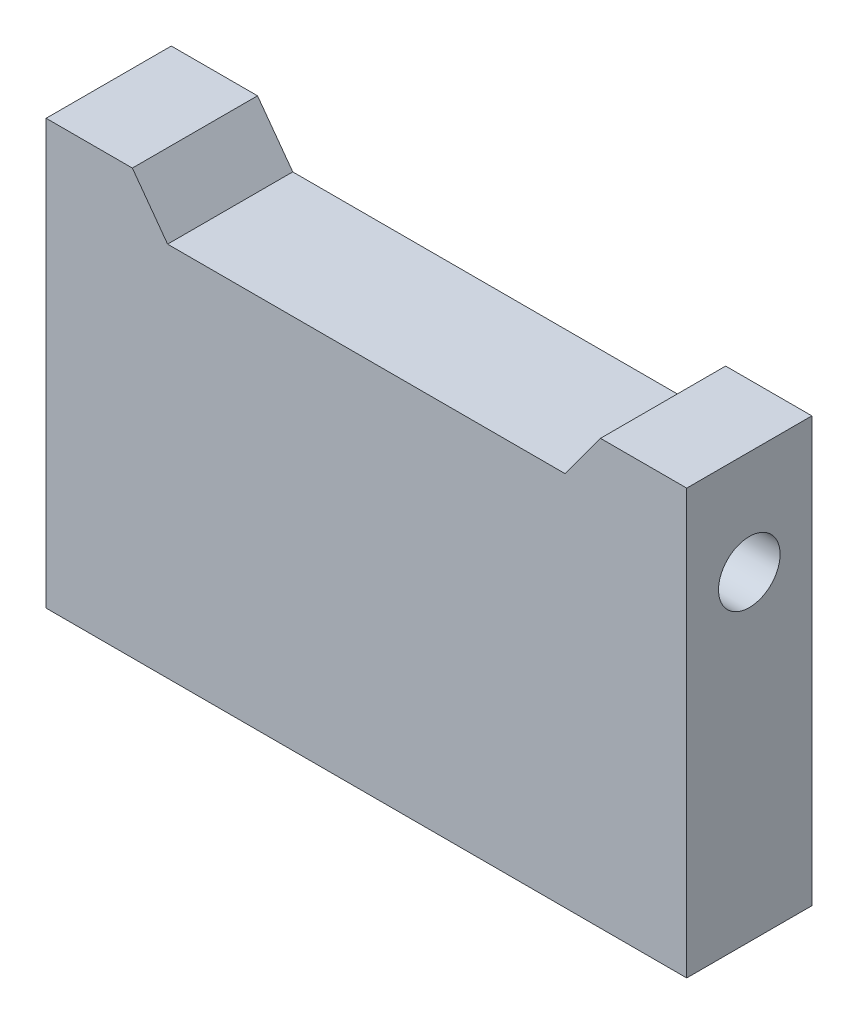
SolidWorks part; units mm, degrees
ref_plane "Piano frontale" through (0, 0, 0) normal (0, 0, 1) x (1, 0, 0)
ref_plane "Piano superiore" through (0, 0, 0) normal (0, 1, 0) x (1, 0, 0)
ref_plane "Piano destro" through (0, 0, 0) normal (1, 0, 0) x (0, 0, -1)
sketch "Schizzo1" plane through (0, 0, 0) normal (0, 0, 1) x (1, 0, 0)
  line L1 (-13, -8.61) -> (13, -8.61)
  line L2 (-13, -8.61) -> (-13, 8.61)
  line L3 (-13, 8.61) -> (13, 8.61)
  line L4 (13, -8.61) -> (13, 8.61)
  line L5 (-13, -8.61) -> (13, 8.61) construction
  line L6 (-13, 8.61) -> (13, -8.61) construction
  point P0 (0, 0)
  dimension "D1" = 26
  dimension "D2" = 17.22
extrude "Estrusione-Estrusione1" add sketch "Schizzo1" against normal blind 5.08
sketch "Schizzo2" plane through (0, 0, 0) normal (0, 0, 1) x (1, 0, 0)
  line L0 (13, 8.61) -> (-13, 8.61) construction
  line L1 (-9.5, 8.61) -> (9.5, 8.61)
  line L2 (0, 8.61) -> (0, -8.61) construction
  line L3 (-13, -8.61) -> (13, -8.61) construction
  line L4 (-9.5, 8.61) -> (-8.07, 6.65)
  line L5 (-8.07, 6.65) -> (8.07, 6.65)
  line L6 (9.5, 8.61) -> (8.07, 6.65)
  line L7 (13, -8.61) -> (13, 8.61) construction
  point P11 (0, 6.65)
  dimension "D1" = 15.26
  dimension "D2" = 4.93
  dimension "D3" = 3.5
extrude "Taglio-Estrusione1" cut sketch "Schizzo2" against normal through all
hole_wizard "Foro filettato M3x0.5-1" positions "Schizzo4" profile "Schizzo3" tap size "M3x0.5" standard "Ansi Metric"
sketch "Schizzo4" plane through (0, -8.61, 0) normal (0, -1, 0) x (-1, 0, 0)
  line L4 (13, 2.54) -> (-13, 2.54) construction
  line L5 (13, 5.08) -> (13, 0) construction
  line L6 (-13, 5.08) -> (-13, 0) construction
  line L7 (0, 0.1779) -> (0, 5.08) construction
  line L8 (13, 5.08) -> (-13, 5.08) construction
  point P0 (10, 2.54)
  point P2 (-10, 2.54)
  dimension "D1" = 20
sketch "Schizzo3" plane through (-10, -8.61, -2.54) normal (1, 0, 0) x (0, 0, -1)
  line L0 (0, 0) -> (0, 8.7511)
  line L1 (0, 8.7511) -> (1.25, 8)
  line L2 (1.25, 8) -> (1.25, 0)
  line L5 (1.25, 0) -> (0, 0)
  line L10 (0, 8.7511) -> (-1.25, 8) construction
  line L11 (0, -6.35) -> (0, 107.95) construction
  dimension "Tap Drill Dia." = 2.5
  dimension "Tap Drill Depth" = 8
  dimension "Drill Angle" = 118
cosmetic thread "Filettatura del foro1" parameters "D1"=8, "D2"=3
cosmetic thread "Filettatura del foro2" parameters "D1"=8, "D2"=3
hole_wizard "Foro filettato M3x0.5-2" positions "Schizzo6" profile "Schizzo5" tap size "M3x0.5" standard "Ansi Metric"
sketch "Schizzo6" plane through (-13, 0, 0) normal (-1, 0, 0) x (0, 0, 1)
  line L0 (-2.54, 8.61) -> (-2.54, -8.61) construction
  line L1 (-5.08, 8.61) -> (0, 8.61) construction
  line L2 (-5.08, -8.61) -> (0, -8.61) construction
  point P0 (-2.54, 4.39)
  dimension "D1" = 13
sketch "Schizzo5" plane through (-13, 4.39, -2.54) normal (0, 1, 0) x (0, 0, 1)
  line L0 (0, 0) -> (0, 6.7511)
  line L1 (0, 6.7511) -> (1.25, 6)
  line L2 (1.25, 6) -> (1.25, 0)
  line L5 (1.25, 0) -> (0, 0)
  line L10 (0, 6.7511) -> (-1.25, 6) construction
  line L11 (0, -6.35) -> (0, 107.95) construction
  dimension "Tap Drill Dia." = 2.5
  dimension "Tap Drill Depth" = 6
  dimension "Drill Angle" = 118
cosmetic thread "Filettatura del foro3" parameters "D1"=6, "D2"=3
mirror "Specchia1" about plane through (0, 0, 0) normal (1, 0, 0) of "Foro filettato M3x0.5-2"
